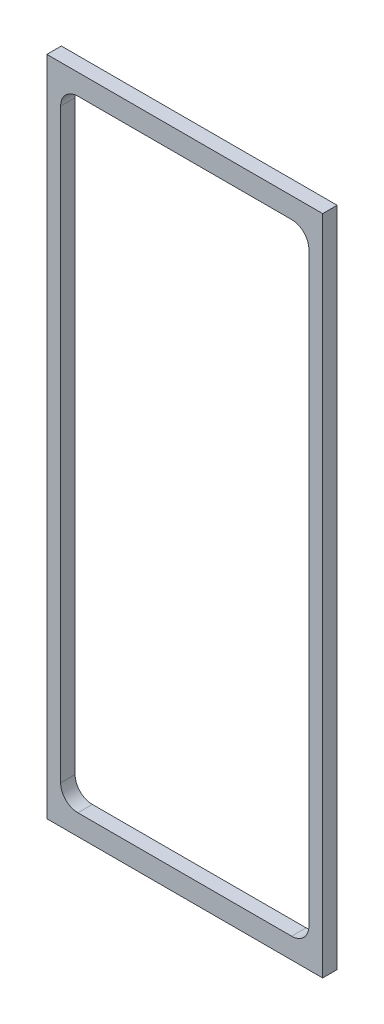
SolidWorks part; units mm, degrees
ref_plane "Front Plane" through (0, 0, 0) normal (0, 0, 1) x (1, 0, 0)
ref_plane "Top Plane" through (0, 0, 0) normal (0, 1, 0) x (1, 0, 0)
ref_plane "Right Plane" through (0, 0, 0) normal (1, 0, 0) x (0, 0, -1)
sketch "Sketch1" plane through (0, 0, 0) normal (0, 0, 1) x (1, 0, 0)
  line L1 (25.4, -60.96) -> (-25.4, -60.96)
  line L2 (25.4, -60.96) -> (25.4, 60.96)
  line L3 (25.4, 60.96) -> (-25.4, 60.96)
  line L4 (-25.4, -60.96) -> (-25.4, 60.96)
  line L5 (25.4, -60.96) -> (-25.4, 60.96) construction
  line L6 (25.4, 60.96) -> (-25.4, -60.96) construction
  point P0 (0, 0)
  dimension "D1" = 121.92
  dimension "D2" = 50.8
extrude "Boss-Extrude1" add sketch "Sketch1" along normal blind 2.667 contours L3 L4 L1 L2
sketch "Sketch2" plane through (0, 0, 2.667) normal (0, 0, 1) x (1, 0, 0)
  line L1 (19.685, -57.15) -> (-19.685, -57.15)
  line L2 (22.86, -53.975) -> (22.86, 53.975)
  line L3 (19.685, 57.15) -> (-19.685, 57.15)
  line L4 (-22.86, -53.975) -> (-22.86, 53.975)
  line L5 (22.86, -57.15) -> (-22.86, 57.15) construction
  line L6 (22.86, 57.15) -> (-22.86, -57.15) construction
  arc A0 (19.685, -57.15) -> (22.86, -53.975) centre (19.685, -53.975) ccw
  arc A1 (-22.86, -53.975) -> (-19.685, -57.15) centre (-19.685, -53.975) ccw
  arc A2 (22.86, 53.975) -> (19.685, 57.15) centre (19.685, 53.975) ccw
  arc A3 (-19.685, 57.15) -> (-22.86, 53.975) centre (-19.685, 53.975) ccw
  point P0 (0, 0)
  dimension "D3" = 3.175
  dimension "D1" = 114.3
  dimension "D2" = 45.72
extrude "Cut-Extrude1" cut sketch "Sketch2" against normal through all
